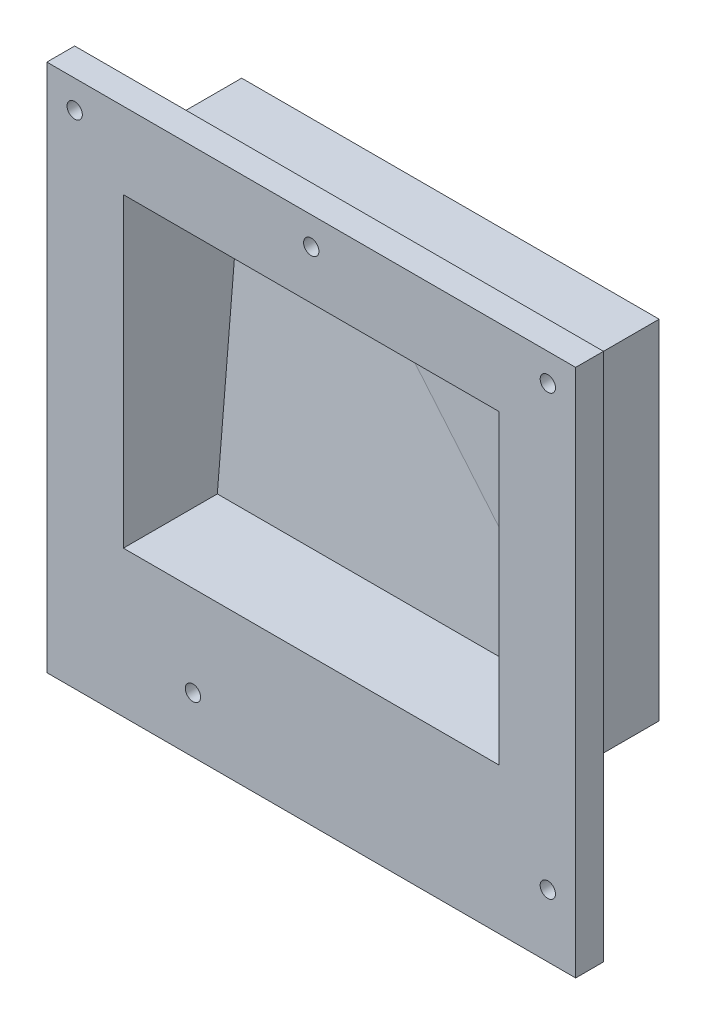
SolidWorks part; units mm, degrees
ref_plane "Front Plane" through (0, 0, 0) normal (0, 0, 1) x (1, 0, 0)
ref_plane "Top Plane" through (0, 0, 0) normal (0, 1, 0) x (1, 0, 0)
ref_plane "Right Plane" through (0, 0, 0) normal (1, 0, 0) x (0, 0, -1)
sketch "Sketch1" plane through (0, 0, 0) normal (0, 0, 1) x (1, 0, 0)
  line L0 (52.5, 170) -> (202.5, 170)
  line L1 (202.5, 170) -> (202.5, 0)
  line L2 (52.5, 170) -> (52.5, 0) construction
  line L3 (52.5, 0) -> (52.5, 45)
  line L4 (52.5, 45) -> (202.5, 45)
  line L5 (52.5, 45) -> (52.5, 170)
  line L6 (32.5, 0) -> (32.5, 45)
  line L7 (32.5, 45) -> (32.5, 190)
  line L8 (32.5, 190) -> (222.5, 190)
  line L9 (222.5, 190) -> (222.5, 0)
  line L10 (32.5, 0) -> (52.5, 0)
  line L11 (52.5, 0) -> (222.5, 0)
  dimension "D1" = 45
  dimension "D2" = 20
extrude "Boss-Extrude1" add sketch "Sketch1" along normal blind 10 contours L1 L11 L9 L8 L7 L6 L10 L3 L5 L0 | L3 L11 L1 L4
sketch "Sketch2" plane through (0, 0, 0) normal (0, 0, -1) x (-1, 0, 0)
  line L0 (-32.5, 0) -> (-222.5, 0) construction
  line L1 (-52.5, 45) -> (-202.5, 45)
  line L2 (-52.5, 45) -> (-52.5, 0)
  line L3 (-52.5, 0) -> (-202.5, 0)
  line L4 (-202.5, 45) -> (-202.5, 0)
  line L5 (-202.5, 0) -> (-202.5, 170) construction
extrude "Boss-Extrude2" add sketch "Sketch2" along normal blind 10
sketch "Sketch3" plane through (0, 0, -10) normal (0, 0, -1) x (-1, 0, 0)
  circle A0 centre (-85, 20) radius 2.75
extrude "Cut-Extrude1" cut sketch "Sketch3" against normal blind 30
sketch "Sketch4" plane through (0, 0, 10) normal (0, 0, 1) x (1, 0, 0)
  line L0 (202.5, 170) -> (222.5, 190)
  line L1 (52.5, 170) -> (32.5, 190)
  line L2 (127.5, 190) -> (127.5, 170)
  line L3 (32.5, 190) -> (222.5, 190) construction
  line L4 (52.5, 170) -> (202.5, 170) construction
  circle A0 centre (42.5, 180) radius 2.75
  circle A1 centre (212.5, 180) radius 2.75
  circle A2 centre (127.5, 180) radius 2.75
  dimension "D1" = 5.5
  dimension "D2" = 5.5
  dimension "D3" = 5.5
extrude "Cut-Extrude2" cut sketch "Sketch4" against normal blind 30 contours L1 A0 | L1 A0 | L2 A2 | L2 A2 | L0 A1 | L0 A1
sketch "Sketch5" plane through (0, 0, 10) normal (0, 0, 1) x (1, 0, 0)
  line L0 (202.5, 45) -> (202.5, 0)
  line L1 (32.5, 0) -> (222.5, 0) construction
  line L2 (202.5, 22.5) -> (222.5, 22.5)
  line L3 (222.5, 190) -> (222.5, 0) construction
  circle A0 centre (212.5, 22.5) radius 2.75
  dimension "D1" = 5.5
extrude "Cut-Extrude3" cut sketch "Sketch5" against normal blind 47 contours L2 A0 | L2 A0
sketch "Sketch7" plane through (0, 0, 10) normal (0, 0, 1) x (1, 0, 0)
  line L0 (60, 162.5) -> (195, 162.5)
  line L1 (52.5, 170) -> (202.5, 170)
  line L2 (52.5, 170) -> (52.5, 45)
  line L3 (52.5, 45) -> (202.5, 45)
  line L4 (202.5, 170) -> (202.5, 45)
  line L5 (195, 162.5) -> (195, 52.5)
  line L6 (60, 52.5) -> (195, 52.5)
  line L7 (60, 162.5) -> (60, 52.5)
  dimension "D1" = 7.5
extrude "Boss-Extrude3" add sketch "Sketch7" against normal blind 50
sketch "Sketch8" plane through (0, 162.5, 0) normal (0, -1, 0) x (1, 0, 0)
  line L0 (60, -40) -> (60, -32.5)
  line L2 (60, -32.5) -> (195, -32.5)
  line L3 (195, -40) -> (195, 10) construction
  line L4 (195, -32.5) -> (195, -40)
  line L5 (195, -40) -> (60, -40)
  dimension "D1" = 7.5
extrude "Boss-Extrude4" add sketch "Sketch8" along normal up to surface (110 mm away) up to face at (127.5, 52.5, -15)
chamfer "Chamfer2" distance 100 angle 5 2 edges at (127.5, 52.5, -32.5) (195, 107.5, -32.5)
